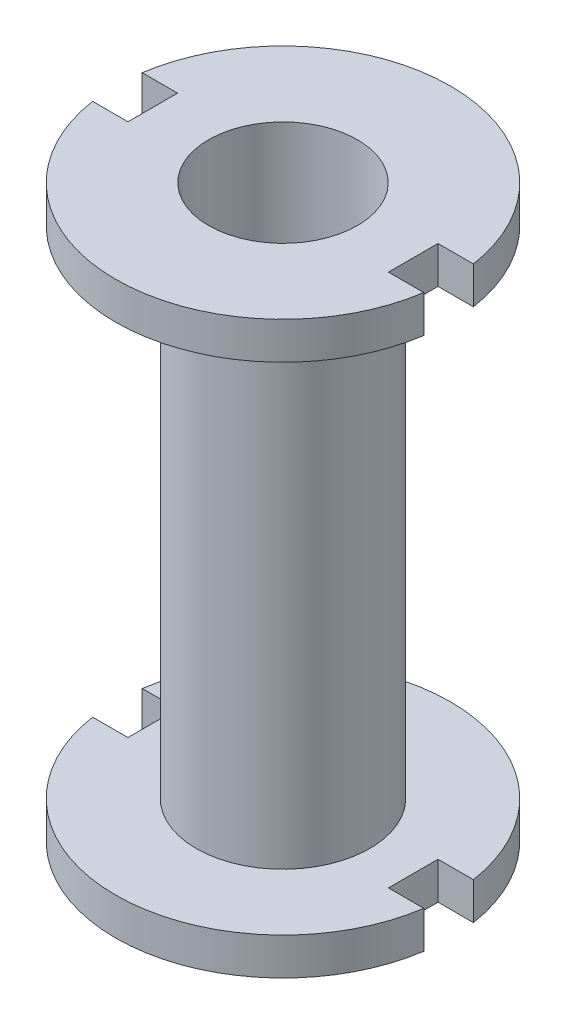
SolidWorks part; units mm, degrees
ref_plane "前视基准面" through (0, 0, 0) normal (0, 0, 1) x (1, 0, 0)
ref_plane "上视基准面" through (0, 0, 0) normal (0, 1, 0) x (1, 0, 0)
ref_plane "右视基准面" through (0, 0, 0) normal (1, 0, 0) x (0, 0, -1)
sketch "草图1" plane through (0, 0, 0) normal (0, 1, 0) x (1, 0, 0)
  circle A0 centre (0, 0) radius 6.75
  circle A1 centre (0, 0) radius 3
  dimension "D1" = 13.5
  dimension "D2" = 6
extrude "凸台-拉伸1" add sketch "草图1" along normal mid plane 23
sketch "草图2" plane through (0, 0, 0) normal (0, 1, 0) x (1, 0, 0)
  circle A0 centre (0, 0) radius 3.5
  circle A1 centre (0, 0) radius 11.3153
  dimension "D1" = 7
extrude "切除-拉伸1" cut sketch "草图2" against normal mid plane 20
sketch "草图4" plane through (0, 11.5, 0) normal (0, 1, 0) x (1, 0, 0)
  line L1 (-8.25, 1) -> (-5.25, 1)
  line L2 (-8.25, 1) -> (-8.25, -1)
  line L3 (-8.25, -1) -> (-5.25, -1)
  line L4 (-5.25, 1) -> (-5.25, -1)
  line L5 (-8.25, 1) -> (-5.25, -1) construction
  line L6 (-8.25, -1) -> (-5.25, 1) construction
  line L7 (5.25, 1) -> (8.25, 1)
  line L8 (5.25, 1) -> (5.25, -1)
  line L9 (5.25, -1) -> (8.25, -1)
  line L10 (8.25, 1) -> (8.25, -1)
  line L11 (5.25, 1) -> (8.25, -1) construction
  line L12 (5.25, -1) -> (8.25, 1) construction
  circle A0 centre (0, 0) radius 6.75 construction
  circle A1 centre (0, 0) radius 6.75 construction
  point P0 (-6.75, 0)
  point P9 (6.75, 0)
  dimension "D1" = 2
  dimension "D2" = 2
  dimension "D3" = 3
  dimension "D4" = 3
extrude "切除-拉伸2" cut sketch "草图4" against normal through all
